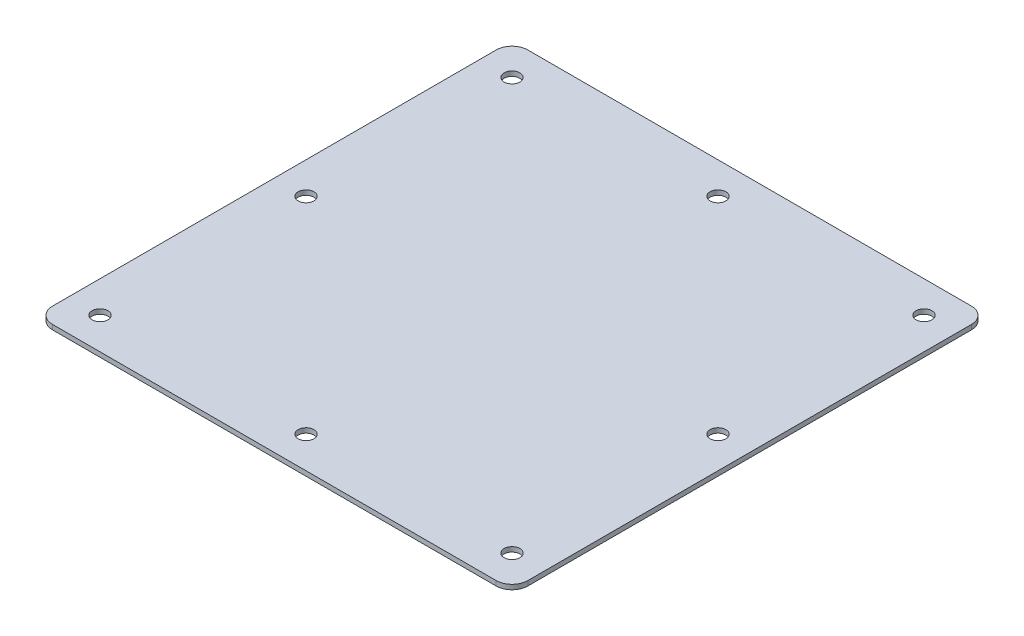
SolidWorks part; units mm, degrees
ref_plane "前视基准面" through (0, 0, 0) normal (0, 0, 1) x (1, 0, 0)
ref_plane "上视基准面" through (0, 0, 0) normal (0, 1, 0) x (1, 0, 0)
ref_plane "右视基准面" through (0, 0, 0) normal (1, 0, 0) x (0, 0, -1)
sketch "草图1" plane through (0, 0, 0) normal (0, 1, 0) x (1, 0, 0)
  line L1 (-150, 150) -> (150, 150)
  line L2 (-150, 150) -> (-150, -150)
  line L3 (-150, -150) -> (150, -150)
  line L4 (150, 150) -> (150, -150)
  dimension "D1" = 300
  dimension "D2" = 300
  dimension "D3" = 150
  dimension "D4" = 150
extrude "凸台-拉伸1" add sketch "草图1" along normal blind 3
fillet "圆角1" radius 10 4 edges at (150, 1.5, -150) (150, 1.5, 150) (-150, 1.5, 150) (-150, 1.5, -150)
sketch "草图2" plane through (0, 3, 0) normal (0, 1, 0) x (1, 0, 0)
  line L0 (140, 150) -> (-140, 150) construction
  line L1 (-150, 140) -> (-150, -140) construction
  circle A0 centre (-130, 130) radius 5
  dimension "D1" = 10
  dimension "D2" = 20
  dimension "D3" = 20
extrude "切除-拉伸1" cut sketch "草图2" against normal through all
mirror "镜向1" about plane through (0, 0, 0) normal (0, 0, 1) of "切除-拉伸1"
mirror "镜向2" about plane through (0, 0, 0) normal (1, 0, 0) of "切除-拉伸1", "镜向1"
sketch "草图3" plane through (0, 3, 0) normal (0, 1, 0) x (1, 0, 0)
  line L0 (-150, 0) -> (150, 0) construction
  line L1 (-150, 140) -> (-150, -140) construction
  line L2 (150, -140) -> (150, 140) construction
  circle A0 centre (-130, 0) radius 5
  dimension "D1" = 10
  dimension "D2" = 20
extrude "切除-拉伸2" cut sketch "草图3" against normal through all
mirror "镜向3" about plane through (0, 0, 0) normal (1, 0, 0) of "切除-拉伸2"
sketch "草图4" plane through (0, 3, 0) normal (0, 1, 0) x (1, 0, 0)
  line L0 (0, 157.8958) -> (0, -156.2183) construction
  line L1 (-130, 130) -> (130, 130) construction
  line L2 (-130, -130) -> (130, -130) construction
  circle A0 centre (0, 130) radius 5
  circle A1 centre (0, -130) radius 5
  dimension "D1" = 10
  dimension "D2" = 10
extrude "切除-拉伸3" cut sketch "草图4" against normal through all
